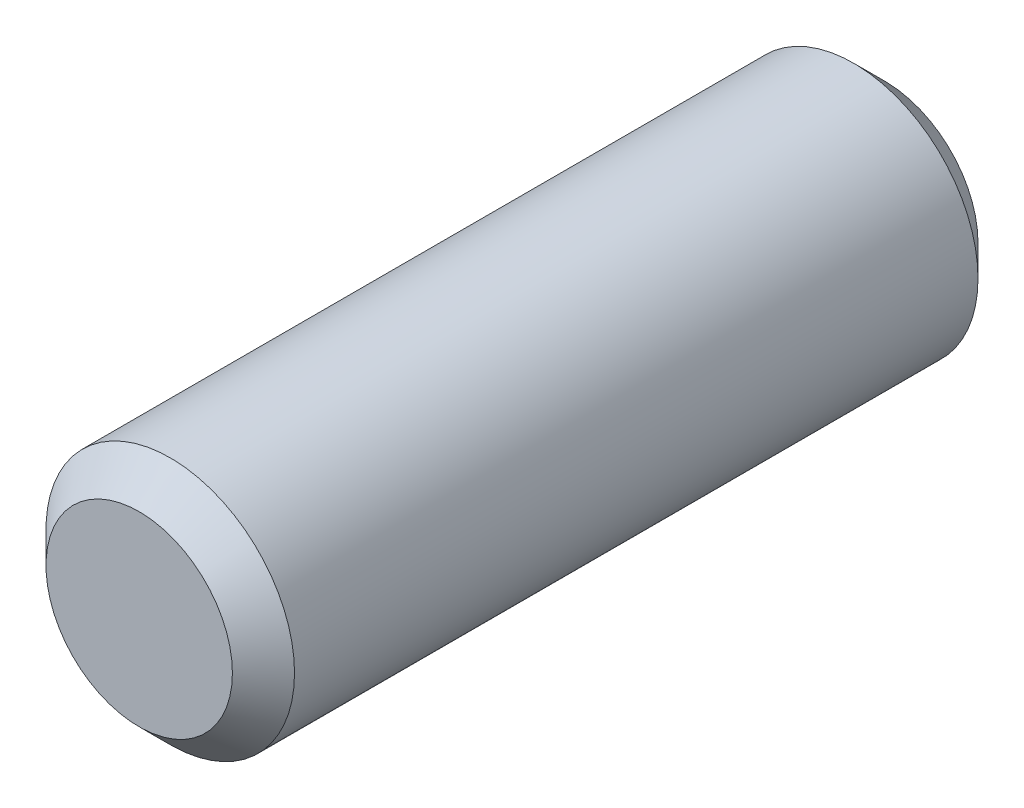
SolidWorks part; units mm, degrees
ref_plane "Front Plane" through (0, 0, 0) normal (0, 0, 1) x (1, 0, 0)
ref_plane "Top Plane" through (0, 0, 0) normal (0, 1, 0) x (1, 0, 0)
ref_plane "Right Plane" through (0, 0, 0) normal (1, 0, 0) x (0, 0, -1)
sketch "Sketch1" plane through (0, 0, 0) normal (0, 0, 1) x (1, 0, 0)
  circle A0 centre (0, 0) radius 1
  dimension "D1" = 2
extrude "Boss-Extrude1" add sketch "Sketch1" along normal mid plane 6
chamfer "Chamfer1" distance 0.25 angle 45 2 edges at (1, 0, -3) (1, 0, 3)
